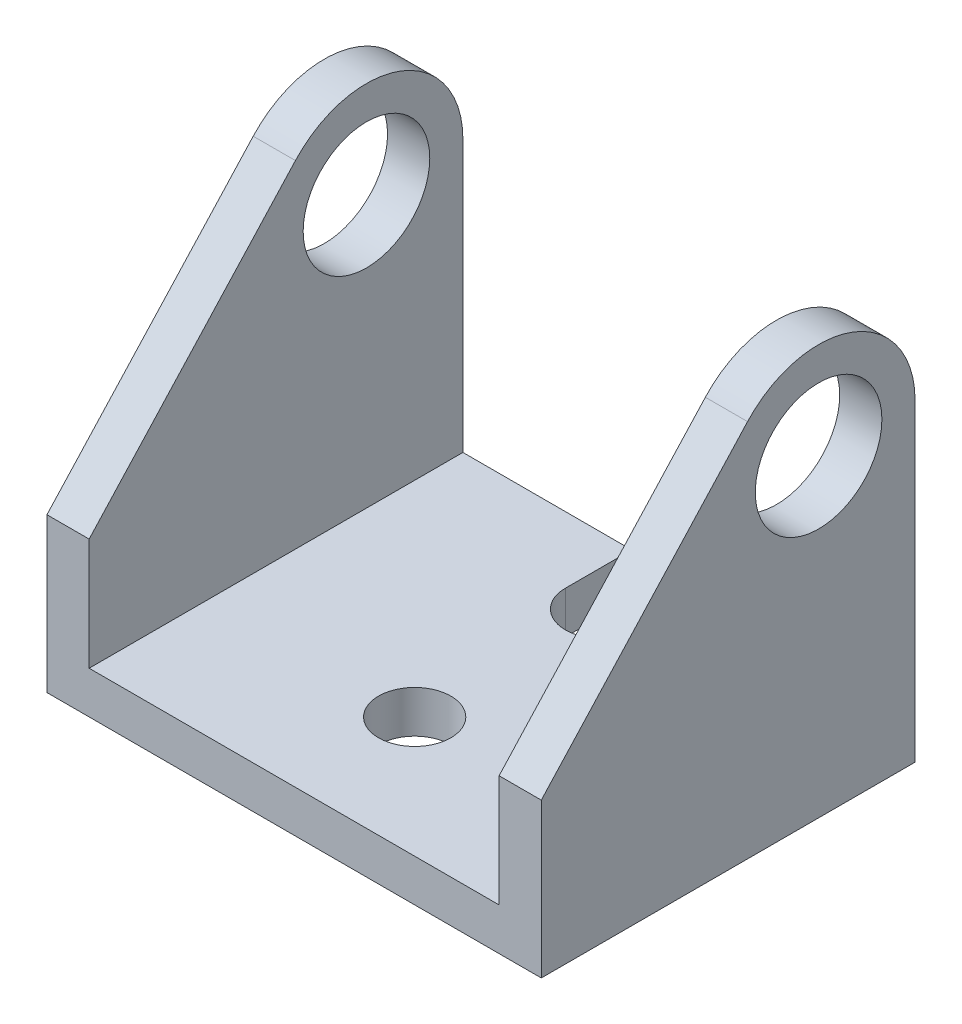
SolidWorks part; units mm, degrees
ref_plane "前视基准面" through (0, 0, 0) normal (0, 0, 1) x (1, 0, 0)
ref_plane "上视基准面" through (0, 0, 0) normal (0, 1, 0) x (1, 0, 0)
ref_plane "右视基准面" through (0, 0, 0) normal (1, 0, 0) x (0, 0, -1)
sketch "草图1" plane through (0, 0, 0) normal (0, 1, 0) x (1, 0, 0)
  line L1 (-20.5, 15.5) -> (20.5, 15.5)
  line L2 (-20.5, 15.5) -> (-20.5, -15.5)
  line L3 (-20.5, -15.5) -> (20.5, -15.5)
  line L4 (20.5, 15.5) -> (20.5, -15.5)
  line L5 (-20.5, 15.5) -> (20.5, -15.5) construction
  line L6 (-20.5, -15.5) -> (20.5, 15.5) construction
  point P0 (0, 0)
  dimension "D1" = 41
  dimension "D2" = 31
extrude "凸台-拉伸1" add sketch "草图1" along normal blind 3.5
sketch "草图2" plane through (0, 3.5, 0) normal (0, 1, 0) x (1, 0, 0)
  line L0 (-20.5, -15.5) -> (20.5, -15.5) construction
  line L1 (-20.5, 15.5) -> (-17, 15.5)
  line L2 (-20.5, 15.5) -> (-20.5, -15.5)
  line L3 (-20.5, -15.5) -> (-17, -15.5)
  line L4 (-17, 15.5) -> (-17, -15.5)
  line L6 (20.5, 15.5) -> (17, 15.5)
  line L7 (20.5, 15.5) -> (20.5, -15.5)
  line L8 (20.5, -15.5) -> (17, -15.5)
  line L9 (17, 15.5) -> (17, -15.5)
  dimension "D1" = 3.5
  dimension "D2" = 3.5
extrude "凸台-拉伸2" add sketch "草图2" along normal blind 40
sketch "草图3" plane through (20.5, 0, 0) normal (1, 0, 0) x (0, 0, -1)
  line L0 (-15.5, 0) -> (15.5, 0) construction
  line L1 (15.5, 43.5) -> (15.5, 0) construction
  line L2 (1.607, 31.4104) -> (-15.5, 12.7772)
  line L3 (-15.5, 43.5) -> (-15.5, 0) construction
  line L4 (-15.5, 12.7772) -> (-15.5, 43.5)
  line L5 (-15.5, 43.5) -> (15.5, 43.5)
  line L6 (15.5, 43.5) -> (15.5, 26)
  circle A0 centre (7.5, 26) radius 5.25
  arc A1 (15.5, 26) -> (1.607, 31.4104) centre (7.5, 26) ccw
  dimension "D1" = 10.5
  dimension "D3" = 16
  dimension "D2" = 26
  dimension "D4" = 8
extrude "切除-拉伸2" cut sketch "草图3" against normal through all
sketch "草图4" plane through (0, 3.5, 0) normal (0, 1, 0) x (1, 0, 0)
  line L0 (0, 23.2042) -> (0, -24.0625) construction
  line L1 (17, 15.5) -> (-17, 15.5) construction
  line L2 (-3, 10) -> (-3, 15.5)
  line L3 (3, 10) -> (3, 15.5)
  line L4 (-3, 15.5) -> (3, 15.5)
  line L5 (-17, -15.5) -> (17, -15.5) construction
  arc A0 (-3, 10) -> (3, 10) centre (0, 10) ccw
  circle A1 centre (0, -5.5) radius 3
  dimension "D1" = 6
  dimension "D3" = 6
  dimension "D2" = 5.5
  dimension "D4" = 10
extrude "切除-拉伸3" cut sketch "草图4" against normal blind 40
